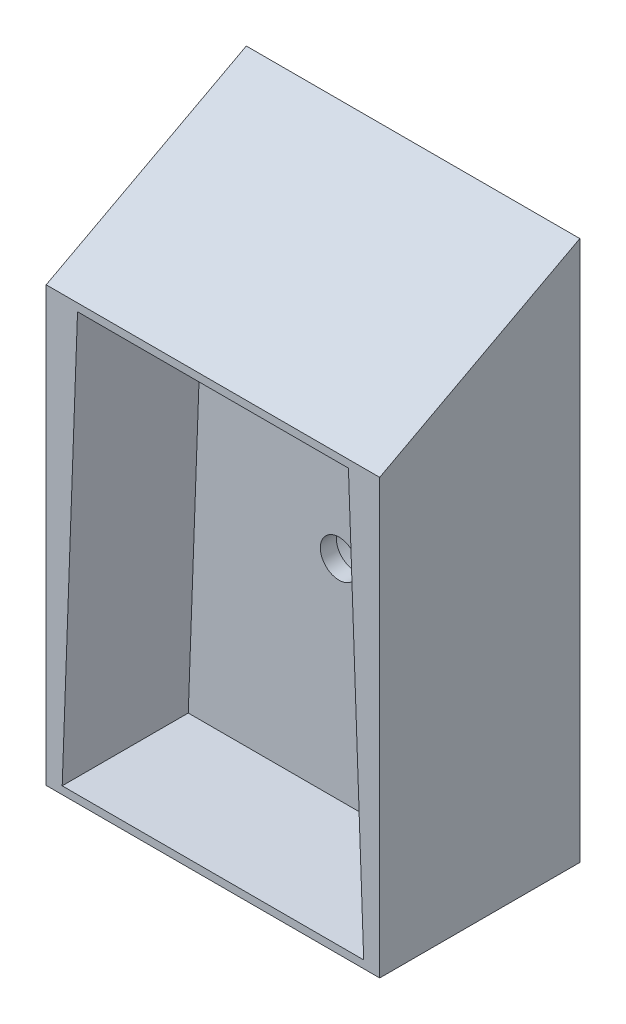
SolidWorks part; units mm, degrees
ref_plane "Přední rovina" through (0, 0, 0) normal (0, 0, 1) x (1, 0, 0)
ref_plane "Horní rovina" through (0, 0, 0) normal (0, 1, 0) x (1, 0, 0)
ref_plane "Pravá rovina" through (0, 0, 0) normal (1, 0, 0) x (0, 0, -1)
sketch "Skica1" plane through (0, 0, 0) normal (0, 0, 1) x (1, 0, 0)
  line L0 (-25, 32.5) -> (25, 32.5)
  line L1 (-25, 32.5) -> (-25, -32.5)
  line L2 (-25, -32.5) -> (25, -32.5)
  line L3 (25, 32.5) -> (25, -32.5)
  dimension "D1" = 50
  dimension "D2" = 65
extrude "Přidat vysunutím1" add sketch "Skica1" along normal blind 30
sketch "Skica3" plane through (25, 0, 0) normal (1, 0, 0) x (0, 0, -1)
  line L0 (0, 32.5) -> (0, 48.5)
  line L1 (0, 48.5) -> (-30, 32.5)
  line L6 (0, -32.5) -> (0, 32.5)
  line L7 (0, 32.5) -> (-30, 32.5)
  line L8 (-30, 32.5) -> (-30, -32.5)
  line L9 (-30, -32.5) -> (0, -32.5)
  line L11 (0, 32.5) -> (-30, 32.5)
  dimension "D1" = 16
  dimension "D2" = 30
  dimension "D3" = 0
extrude "Přidat vysunutím2" add sketch "Skica3" against normal through all
sketch "Skica5" plane through (0, 0, 30) normal (0, 0, 1) x (1, 0, 0)
  line L0 (-20.3, 31.35) -> (20.31, 31.35)
  line L2 (-25, -32.5) -> (25, -32.5) construction
  line L3 (20.31, 31.35) -> (22.6, -31.35)
  line L5 (-20.3, 31.35) -> (20.31, 31.35) construction
  line L7 (22.6, -31.35) -> (-22.6, -31.35)
  line L11 (-20.3, 31.35) -> (-22.6, -31.35)
  line L12 (-25, 32.5) -> (-25, -32.5) construction
  dimension "D1" = 45.2
  dimension "D2" = 40.61
  dimension "D3" = 1.15
  dimension "D4" = 4.7
  dimension "D5" = 62.7
  dimension "D6" = 2.4
extrude "Odebrat vysunutím1" cut sketch "Skica5" against normal offset from surface (18.9 mm away) 18.9 up to face at (0, 0, 30)
sketch "Skica6" plane through (0, 0, 11.1) normal (0, 0, 1) x (1, 0, 0)
  line L2 (22.6, -31.35) -> (-22.6, -31.35) construction
  circle A0 centre (0, 0) radius 2.8
  point P0 (0, -1.85)
  dimension "D2" = 5.6
  dimension "D1" = 29.5
extrude "Odebrat vysunutím2" cut sketch "Skica6" against normal through all
sketch "Skica7" plane through (0, 0, 0) normal (0, 0, -1) x (-1, 0, 0)
  circle A0 centre (0, 0) radius 7.5
  dimension "D1" = 15
extrude "Odebrat vysunutím3" cut sketch "Skica7" against normal blind 8.7
sketch "Skica8" plane through (0, 0, 0) normal (0, 0, -1) x (-1, 0, 0)
  line L0 (-25, 15.3) -> (25, 15.3) construction
  line L1 (-25, -32.5) -> (-25, 48.5) construction
  line L2 (25, 48.5) -> (25, -32.5) construction
  line L3 (25, 48.5) -> (-25, 48.5) construction
  line L4 (0, 15.3) -> (0, 48.5) construction
  line L5 (0, 31.9) -> (25, 31.9) construction
  line L6 (0, 31.9) -> (-25, 31.9) construction
  circle A0 centre (7.149, 26.6072) radius 2.35
  circle A1 centre (-7.149, 26.6072) radius 2.35
  circle A2 centre (7.149, 37.1928) radius 2.35
  circle A3 centre (-7.149, 37.1928) radius 2.35
  point P15 (3.1581, 28.5456)
  point P22 (-7.149, 26.6072)
  point P23 (0, 0)
  point P25 (7.3194, 36.8747)
  dimension "D2" = 4.7
  dimension "D3" = 10.5856
  dimension "D4" = 17.851
  dimension "D5" = 11.3072
  dimension "D1" = 33.2
extrude "Odebrat vysunutím4" cut sketch "Skica8" against normal blind 8.5
